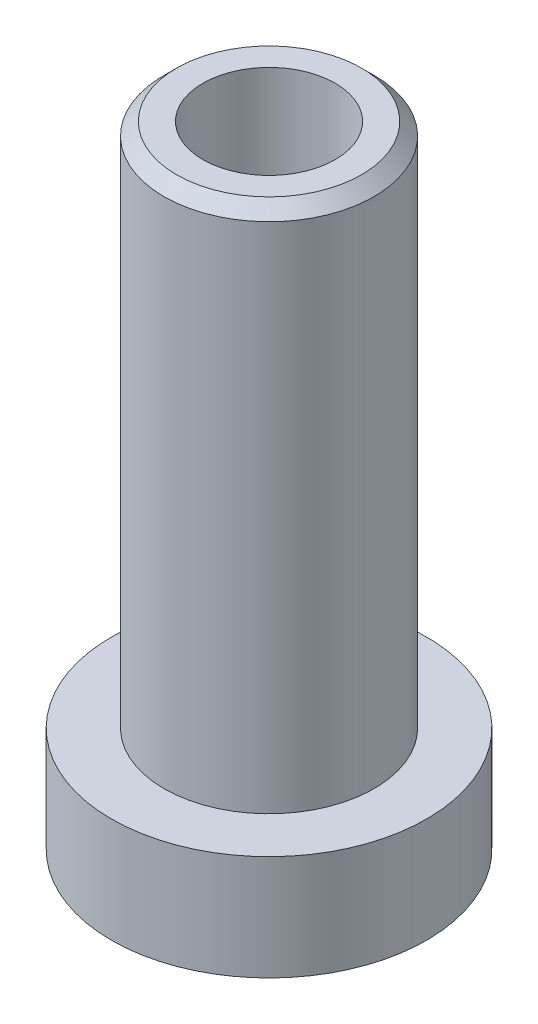
SolidWorks part; units mm, degrees
ref_plane "Front Plane" through (0, 0, 0) normal (0, 0, 1) x (1, 0, 0)
ref_plane "Top Plane" through (0, 0, 0) normal (0, 1, 0) x (1, 0, 0)
ref_plane "Right Plane" through (0, 0, 0) normal (1, 0, 0) x (0, 0, -1)
sketch "Sketch1" plane through (0, 0, 0) normal (0, 1, 0) x (1, 0, 0)
  circle A0 centre (0, 0) radius 0.75
  dimension "D1" = 1.5
extrude "Boss-Extrude1" add sketch "Sketch1" along normal blind 0.5
sketch "Sketch2" plane through (0, 0.5, 0) normal (0, 1, 0) x (1, 0, 0)
  circle A0 centre (0, 0) radius 0.5
  dimension "D1" = 1
extrude "Boss-Extrude2" add sketch "Sketch2" along normal blind 2.5
chamfer "Chamfer1" distance 0.06 angle 45 1 edges at (0, 3, 0.5)
sketch "Sketch3" plane through (0, 0, 0) normal (0, -1, 0) x (1, 0, 0)
  circle A0 centre (0, 0) radius 0.315
  dimension "D1" = 0.63
extrude "Cut-Extrude1" cut sketch "Sketch3" against normal up to next
